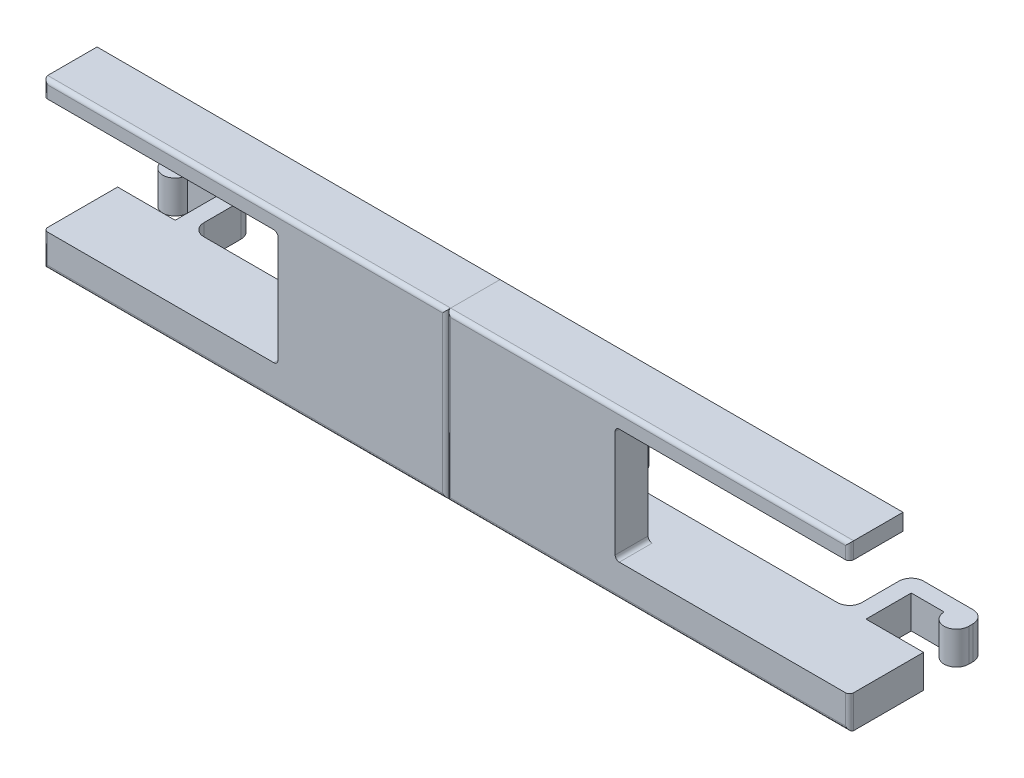
SolidWorks part; units mm, degrees
ref_plane "前视基准面" through (0, 0, 0) normal (0, 0, 1) x (1, 0, 0)
ref_plane "上视基准面" through (0, 0, 0) normal (0, 1, 0) x (1, 0, 0)
ref_plane "右视基准面" through (0, 0, 0) normal (1, 0, 0) x (0, 0, -1)
sketch "草图1" plane through (0, 0, 0) normal (0, 1, 0) x (1, 0, 0)
  line L1 (-41.2542, 7.7769) -> (-34.2542, 7.7769)
  line L2 (-41.2542, 7.7769) -> (-41.2542, -1.2231)
  line L3 (-41.2542, -1.2231) -> (7.7458, -1.2231)
  line L4 (7.7458, 7.7769) -> (7.7458, -1.2231)
  line L6 (7.7458, 7.7769) -> (7.7458, 15.2769)
  line L7 (7.7458, 15.2769) -> (5.7458, 15.2769)
  line L9 (5.7458, 15.2769) -> (-1.2542, 15.2769)
  line L11 (5.7458, 13.2769) -> (1.7458, 13.2769)
  line L12 (-1.2542, 15.2769) -> (-1.2542, 13.2769)
  line L13 (-32.2542, 7.7769) -> (-32.2542, 15.2769)
  line L14 (-32.2542, 15.2769) -> (-34.2542, 15.2769)
  line L15 (-34.2542, 7.7769) -> (-34.2542, 13.2769)
  line L16 (-34.2542, 15.2769) -> (-41.2542, 15.2769)
  line L18 (-34.2542, 13.2769) -> (-38.2542, 13.2769)
  line L19 (-41.2542, 15.2769) -> (-41.2542, 13.2769)
  line L20 (-32.2542, 7.7769) -> (5.7458, 7.7769)
  line L23 (7.7458, 7.7769) -> (7.7458, 12.7769)
  line L25 (5.7458, 7.7769) -> (5.7458, 13.2769)
  arc A0 (-1.2542, 13.2769) -> (1.7458, 13.2769) centre (0.2458, 13.2769) ccw
  arc A1 (-41.2542, 13.2769) -> (-38.2542, 13.2769) centre (-39.7542, 13.2769) ccw
  dimension "D7" = 3
  dimension "D10" = 3
  dimension "D1" = 49
  dimension "D2" = 9
  dimension "D3" = 7.5
  dimension "D4" = 9
  dimension "D5" = 9
  dimension "D6" = 2
  dimension "D12" = 0
  dimension "D13" = 7.5
extrude "凸台-拉伸1" add sketch "草图1" along normal blind 4
fillet "圆角1" radius 1.5 4 edges at (7.7458, 2, -15.2769) (-1.2542, 2, -15.2769) (-32.2542, 2, -15.2769) (-41.2542, 2, -15.2769)
sketch "草图2" plane through (0, 4, 0) normal (0, 1, 0) x (1, 0, 0)
  line L1 (7.7458, -1.2231) -> (-0.7542, -1.2231)
  line L2 (7.7458, -1.2231) -> (7.7458, 5.2769)
  line L3 (7.7458, 5.2769) -> (-0.7542, 5.2769)
  line L4 (-0.7542, 2.7769) -> (-0.7542, 5.2769)
  line L5 (-0.7542, -1.2231) -> (-12.7542, -1.2231)
  line L7 (-0.7542, 2.7769) -> (-12.7542, 2.7769)
  line L8 (-12.7542, -1.2231) -> (-12.7542, 2.7769)
  dimension "D1" = 6.5
  dimension "D2" = 8.5
  dimension "D3" = 12
  dimension "D4" = 4
extrude "凸台-拉伸2" add sketch "草图2" along normal blind 14
sketch "草图3" plane through (0, 18, 0) normal (0, 1, 0) x (1, 0, 0)
  line L0 (-41.2542, 7.7769) -> (-41.2542, -1.2231) construction
  line L1 (7.7458, -1.2231) -> (-41.2542, -1.2231)
  line L2 (7.7458, -1.2231) -> (7.7458, 5.2769)
  line L3 (7.7458, 5.2769) -> (-41.2542, 5.2769)
  line L4 (-41.2542, -1.2231) -> (-41.2542, 5.2769)
  dimension "D1" = 6.5
extrude "凸台-拉伸3" add sketch "草图3" along normal blind 2
fillet "圆角2" radius 0.5 8 edges at (-41.2542, 19, 1.2231) (-41.2542, 2, 1.2231) (-16.7542, 0, 1.2231) (-16.7542, 20, 1.2231) (7.7458, 10, 1.2231) (-0.7542, 11, -2.7769) (-12.7542, 4, -0.7769) (-12.7542, 18, -0.7769)
fillet "圆角3" radius 1.5 1 edges at (-32.2542, 2, -7.7769)
mirror "镜向1" about plane through (7.7458, 4, 0) normal (1, 0, 0) of bodies 110
